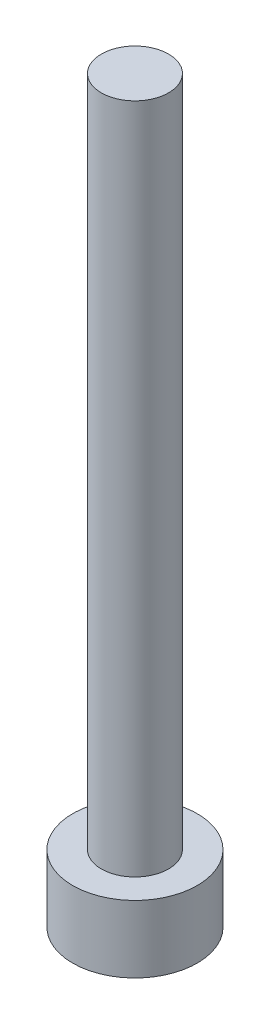
SolidWorks part; units mm, degrees
ref_plane "Front Plane" through (0, 0, 0) normal (0, 0, 1) x (1, 0, 0)
ref_plane "Top Plane" through (0, 0, 0) normal (0, 1, 0) x (1, 0, 0)
ref_plane "Right Plane" through (0, 0, 0) normal (1, 0, 0) x (0, 0, -1)
sketch "Sketch1" plane through (0, 0, 0) normal (0, 1, 0) x (1, 0, 0)
  circle A0 centre (0, 0) radius 2.78
  dimension "D1" = 5.56
extrude "Boss-Extrude1" add sketch "Sketch1" along normal blind 3
sketch "Sketch2" plane through (0, 3, 0) normal (0, 1, 0) x (1, 0, 0)
  circle A0 centre (0, 0) radius 1.5
  dimension "D1" = 3
extrude "Boss-Extrude2" add sketch "Sketch2" along normal blind 30
